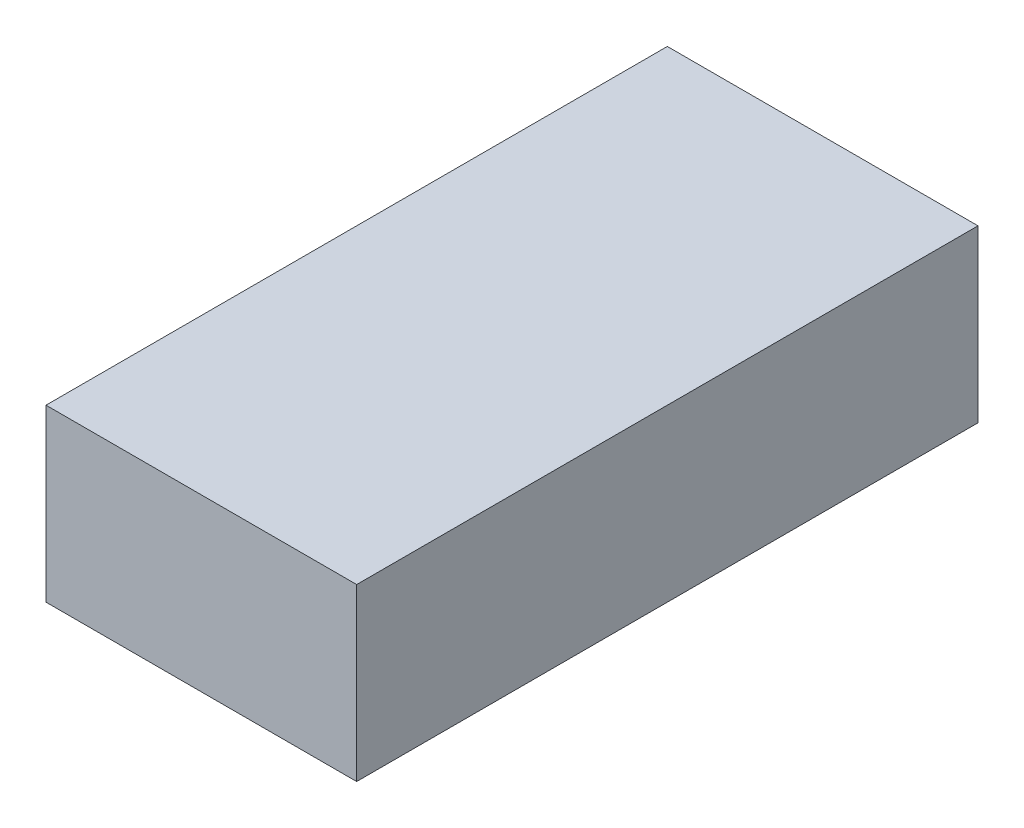
SolidWorks part; units mm, degrees
ref_plane "Front Plane" through (0, 0, 0) normal (0, 0, 1) x (1, 0, 0)
ref_plane "Top Plane" through (0, 0, 0) normal (0, 1, 0) x (1, 0, 0)
ref_plane "Right Plane" through (0, 0, 0) normal (1, 0, 0) x (0, 0, -1)
sketch "Sketch1" plane through (0, 0, 0) normal (0, 1, 0) x (1, 0, 0)
  line L1 (-2.54, -5.08) -> (2.54, -5.08)
  line L2 (-2.54, -5.08) -> (-2.54, 5.08)
  line L3 (-2.54, 5.08) -> (2.54, 5.08)
  line L4 (2.54, -5.08) -> (2.54, 5.08)
  line L5 (-2.54, -5.08) -> (2.54, 5.08) construction
  line L6 (-2.54, 5.08) -> (2.54, -5.08) construction
  point P0 (0, 0)
  dimension "D1" = 10.16
  dimension "D2" = 5.08
extrude "Boss-Extrude1" add sketch "Sketch1" along normal blind 2.79
